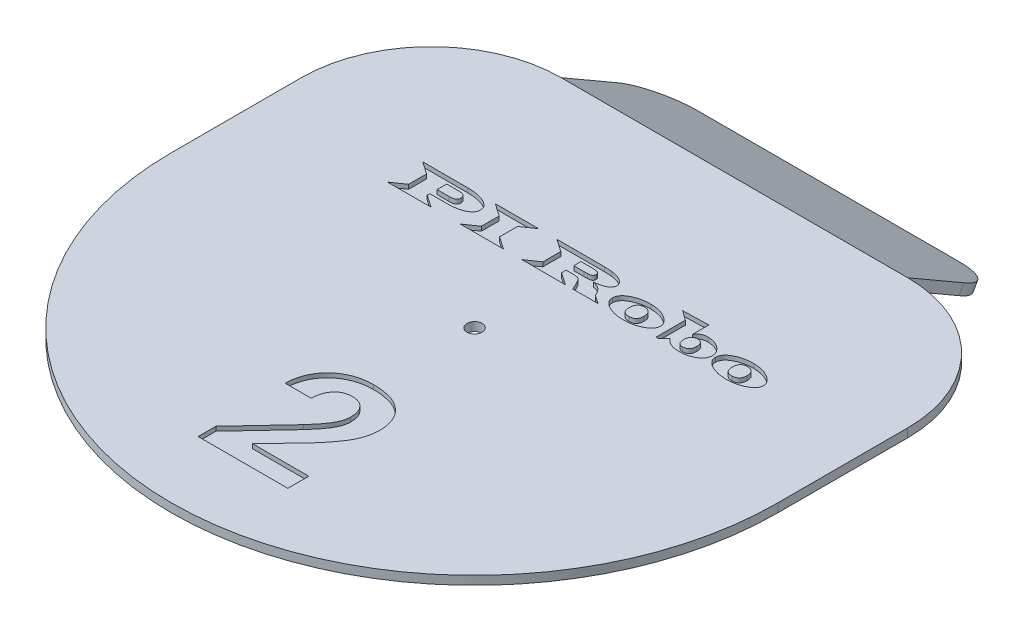
SolidWorks part; units mm, degrees
ref_plane "Front Plane" through (0, 0, 0) normal (0, 0, 1) x (1, 0, 0)
ref_plane "Top Plane" through (0, 0, 0) normal (0, 1, 0) x (1, 0, 0)
ref_plane "Right Plane" through (0, 0, 0) normal (1, 0, 0) x (0, 0, -1)
sketch "Sketch1" plane through (0, 0, 0) normal (0, 1, 0) x (1, 0, 0)
  line L0 (-70, 0) -> (-70, 30)
  line L1 (-40, 60) -> (40, 60)
  line L2 (70, 30) -> (70, 0)
  arc A0 (-70, 0) -> (70, 0) centre (0, 0) ccw
  arc A1 (40, 60) -> (70, 30) centre (40, 30) cw
  arc A2 (-70, 30) -> (-40, 60) centre (-40, 30) cw
  dimension "D1" = 140
  dimension "D3" = 30
  dimension "D2" = 60
extrude "Boss-Extrude1" add sketch "Sketch1" along normal blind 2
sketch "Sketch2" plane through (0, 2, 0) normal (0, 1, 0) x (1, 0, 0)
  text T0 "<b>PI Robo</b>" font "Wide Latin" height 8
  text T1 "<b>2</b>\r\n" font "IRANSans" height 30
extrude "Cut-Extrude1" cut sketch "Sketch2" against normal blind 1
sketch "Sketch3" plane through (0, 0, 0) normal (1, 0, 0) x (0, 0, -1)
  line L0 (60, 2) -> (58.8453, 0)
  line L1 (60, 2) -> (81.6506, -10.5)
  line L2 (58.8453, 0) -> (80.4959, -12.5)
  line L3 (81.6506, -10.5) -> (80.4959, -12.5)
  line L4 (30, 0) -> (60, 0) construction
  line L5 (60, 2) -> (30, 2) construction
  dimension "D1" = 25
  dimension "D2" = 30
extrude "Boss-Extrude2" add sketch "Sketch3" along normal blind 40 and the other way blind 40
fillet "Fillet1" radius 10 2 edges at (-40, -11.5, -81.0733) (40, -11.5, -81.0733)
sketch "Sketch4" plane through (0, 2, 0) normal (0, 1, 0) x (1, 0, 0)
  circle A0 centre (0, 0) radius 1.75
  dimension "D1" = 3.5
extrude "Cut-Extrude2" cut sketch "Sketch4" against normal blind 10
